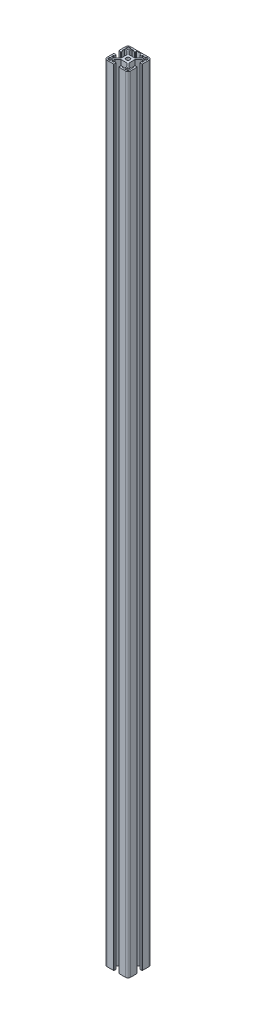
SolidWorks part; units mm, degrees
ref_plane "Front Plane" through (0, 0, 0) normal (0, 0, 1) x (1, 0, 0)
ref_plane "Top Plane" through (0, 0, 0) normal (0, 1, 0) x (1, 0, 0)
ref_plane "Right Plane" through (0, 0, 0) normal (1, 0, 0) x (0, 0, -1)
sketch "Sketch2" plane through (0, 0, 0) normal (0, 1, 0) x (1, 0, 0)
  line L0 (3.6, -15) -> (12, -15)
  line L1 (15, -12) -> (15, -3.6)
  line L2 (14.5, -3.1) -> (12.5, -3.1)
  line L3 (12, -3.6) -> (12, -5.6)
  line L4 (12, -5.6) -> (12.5, -5.6)
  line L5 (13, -6.1) -> (13, -8.25)
  line L6 (13, -8.25) -> (10.4926, -8.25)
  line L7 (9.0784, -7.6642) -> (5.25, -3.8358)
  line L9 (3.8358, -5.25) -> (7.4142, -8.8284)
  line L10 (8, -10.2426) -> (8, -13)
  line L11 (8, -13) -> (6.1, -13)
  line L12 (5.6, -12.5) -> (5.6, -12)
  line L13 (5.6, -12) -> (3.6, -12)
  line L14 (3.1, -12.5) -> (3.1, -14.5)
  line L15 (0, 0) -> (0, 2.5) construction
  line L16 (-3.8358, 5.25) -> (3.8358, 5.25)
  line L17 (-5.25, 3.8358) -> (-5.25, -3.8358)
  line L18 (-3.8358, -5.25) -> (3.8358, -5.25)
  line L19 (5.25, 3.8358) -> (5.25, -3.8358)
  line L20 (-1.7678, 1.7678) -> (8.7215, -8.7215) construction
  line L21 (-1.7678, -1.7678) -> (1.7678, 1.7678) construction
  line L22 (9.5, -9.75) -> (13.25, -9.75)
  line L23 (9.5, -9.75) -> (9.5, -13.5)
  line L24 (9.5, -13.5) -> (11.25, -13.5)
  line L25 (13.25, -9.75) -> (13.25, -11.5)
  line L26 (0, 0) -> (-2.5, 0) construction
  line L27 (-3.1, -12.5) -> (-3.1, -14.5)
  line L28 (-5.6, -12) -> (-3.6, -12)
  line L29 (-5.6, -12.5) -> (-5.6, -12)
  line L30 (-13.25, -9.75) -> (-13.25, -11.5)
  line L31 (-9.5, -13.5) -> (-11.25, -13.5)
  line L32 (-9.5, -9.75) -> (-9.5, -13.5)
  line L33 (-9.5, -9.75) -> (-13.25, -9.75)
  line L34 (-8, -13) -> (-6.1, -13)
  line L35 (-8, -10.2426) -> (-8, -13)
  line L36 (-3.8358, -5.25) -> (-7.4142, -8.8284)
  line L37 (-9.0784, -7.6642) -> (-5.25, -3.8358)
  line L38 (-13, -8.25) -> (-10.4926, -8.25)
  line L39 (-13, -6.1) -> (-13, -8.25)
  line L40 (-12, -5.6) -> (-12.5, -5.6)
  line L41 (-12, -3.6) -> (-12, -5.6)
  line L42 (-14.5, -3.1) -> (-12.5, -3.1)
  line L43 (-15, -12) -> (-15, -3.6)
  line L44 (-3.6, -15) -> (-12, -15)
  line L45 (3.1, 12.5) -> (3.1, 14)
  line L46 (5.6, 12) -> (3.6, 12)
  line L47 (5.6, 12.5) -> (5.6, 12)
  line L48 (-5.6, 12.5) -> (-5.6, 12)
  line L49 (-5.6, 12) -> (-3.6, 12)
  line L50 (-3.1, 12.5) -> (-3.1, 14)
  line L52 (-8, 13) -> (-6.1, 13)
  line L53 (-3.8358, 5.25) -> (-7.4142, 8.8284)
  line L54 (-9.0784, 7.6642) -> (-5.25, 3.8358)
  line L55 (-15, 12) -> (-15, 3.6)
  line L56 (-14.5, 3.1) -> (-12.5, 3.1)
  line L57 (-12, 3.6) -> (-12, 5.6)
  line L58 (-12, 5.6) -> (-12.5, 5.6)
  line L59 (-13, 6.1) -> (-13, 8.25)
  line L60 (-13, 8.25) -> (-10.4926, 8.25)
  line L61 (-8, 10.2426) -> (-8, 13)
  line L62 (-9.5, 9.75) -> (-13.25, 9.75)
  line L63 (-9.5, 9.75) -> (-9.5, 13.5)
  line L64 (-9.5, 13.5) -> (-11.25, 13.5)
  line L65 (-13.25, 9.75) -> (-13.25, 11.5)
  line L66 (13.25, 9.75) -> (13.25, 11.5)
  line L67 (9.5, 13.5) -> (11.25, 13.5)
  line L68 (9.5, 9.75) -> (9.5, 13.5)
  line L69 (9.5, 9.75) -> (13.25, 9.75)
  line L70 (8, 13) -> (6.1, 13)
  line L71 (8, 10.2426) -> (8, 13)
  line L72 (3.8358, 5.25) -> (7.4142, 8.8284)
  line L73 (9.0784, 7.6642) -> (5.25, 3.8358)
  line L74 (13, 8.25) -> (10.4926, 8.25)
  line L75 (13, 6.1) -> (13, 8.25)
  line L76 (12, 5.6) -> (12.5, 5.6)
  line L77 (12, 3.6) -> (12, 5.6)
  line L78 (14.5, 3.1) -> (12.5, 3.1)
  line L79 (15, 12) -> (15, 3.6)
  line L81 (0, 5.25) -> (0, 9.0083) construction
  line L82 (-5.25, 0) -> (-10.2369, 0) construction
  line L83 (12, 15) -> (-12, 15)
  line L86 (-3.1, 14) -> (3.1, 14)
  circle A0 centre (0, 0) radius 2.5
  arc A1 (7.4142, -8.8284) -> (8, -10.2426) centre (6, -10.2426) cw
  arc A2 (10.4926, -8.25) -> (9.0784, -7.6642) centre (10.4926, -6.25) cw
  arc A5 (15, -3.6) -> (14.5, -3.1) centre (14.5, -3.6) ccw
  arc A6 (12.5, -3.1) -> (12, -3.6) centre (12.5, -3.6) ccw
  arc A7 (12.5, -5.6) -> (13, -6.1) centre (12.5, -6.1) cw
  arc A8 (6.1, -13) -> (5.6, -12.5) centre (6.1, -12.5) cw
  arc A9 (3.6, -15) -> (3.1, -14.5) centre (3.6, -14.5) cw
  arc A10 (3.6, -12) -> (3.1, -12.5) centre (3.6, -12.5) ccw
  arc A11 (12, -15) -> (15, -12) centre (12, -12) ccw
  arc A12 (11.25, -13.5) -> (13.25, -11.5) centre (11.25, -11.5) ccw
  arc A13 (-3.6, -15) -> (-3.1, -14.5) centre (-3.6, -14.5) ccw
  arc A14 (-3.6, -12) -> (-3.1, -12.5) centre (-3.6, -12.5) cw
  arc A15 (-6.1, -13) -> (-5.6, -12.5) centre (-6.1, -12.5) ccw
  arc A16 (-11.25, -13.5) -> (-13.25, -11.5) centre (-11.25, -11.5) cw
  arc A17 (-12, -15) -> (-15, -12) centre (-12, -12) cw
  arc A18 (-12.5, -5.6) -> (-13, -6.1) centre (-12.5, -6.1) ccw
  arc A19 (-12.5, -3.1) -> (-12, -3.6) centre (-12.5, -3.6) cw
  arc A20 (-15, -3.6) -> (-14.5, -3.1) centre (-14.5, -3.6) cw
  arc A21 (-10.4926, -8.25) -> (-9.0784, -7.6642) centre (-10.4926, -6.25) ccw
  arc A22 (-7.4142, -8.8284) -> (-8, -10.2426) centre (-6, -10.2426) ccw
  arc A24 (3.6, 12) -> (3.1, 12.5) centre (3.6, 12.5) cw
  arc A25 (6.1, 13) -> (5.6, 12.5) centre (6.1, 12.5) ccw
  arc A26 (-3.6, 12) -> (-3.1, 12.5) centre (-3.6, 12.5) ccw
  arc A28 (-6.1, 13) -> (-5.6, 12.5) centre (-6.1, 12.5) cw
  arc A29 (-7.4142, 8.8284) -> (-8, 10.2426) centre (-6, 10.2426) cw
  arc A30 (-10.4926, 8.25) -> (-9.0784, 7.6642) centre (-10.4926, 6.25) cw
  arc A31 (-15, 3.6) -> (-14.5, 3.1) centre (-14.5, 3.6) ccw
  arc A32 (-12.5, 3.1) -> (-12, 3.6) centre (-12.5, 3.6) ccw
  arc A33 (-12.5, 5.6) -> (-13, 6.1) centre (-12.5, 6.1) cw
  arc A34 (-12, 15) -> (-15, 12) centre (-12, 12) ccw
  arc A35 (-11.25, 13.5) -> (-13.25, 11.5) centre (-11.25, 11.5) ccw
  arc A36 (11.25, 13.5) -> (13.25, 11.5) centre (11.25, 11.5) cw
  arc A37 (12, 15) -> (15, 12) centre (12, 12) cw
  arc A38 (12.5, 5.6) -> (13, 6.1) centre (12.5, 6.1) ccw
  arc A39 (12.5, 3.1) -> (12, 3.6) centre (12.5, 3.6) cw
  arc A40 (15, 3.6) -> (14.5, 3.1) centre (14.5, 3.6) cw
  arc A41 (10.4926, 8.25) -> (9.0784, 7.6642) centre (10.4926, 6.25) ccw
  arc A42 (7.4142, 8.8284) -> (8, 10.2426) centre (6, 10.2426) ccw
  point P34 (13.25, -13.5)
  point P37 (5.6, -12.25)
  point P40 (15, -3.1)
  point P43 (12, -3.1)
  point P50 (3.1, -15)
  point P53 (3.1, -12)
  point P54 (3.1, -13.5)
  point P58 (-3.1, -13.5)
  point P62 (-3.1, -12)
  point P64 (-5.6, -12.25)
  point P97 (-12, -3.1)
  point P98 (-15, -3.1)
  point P99 (-13.25, -13.5)
  point P149 (-13.25, 13.5)
  point P150 (-15, 3.1)
  point P151 (-12, 3.1)
  point P181 (12, 3.1)
  point P182 (15, 3.1)
  point P183 (13.25, 13.5)
  dimension "D1" = 5
  dimension "D22" = 2
  dimension "D23" = 0.5
  dimension "D24" = 3
  dimension "D25" = 2
  dimension "D30" = 7.6716
  dimension "D3" = 30
  dimension "D4" = 30
  dimension "D5" = 1
  dimension "D6" = 3.1
  dimension "D7" = 3
  dimension "D8" = 2
  dimension "D9" = 9.75
  dimension "D10" = 9.75
  dimension "D11" = 3
  dimension "D12" = 2
  dimension "D13" = 6.75
  dimension "D14" = 7
  dimension "D15" = 3.75
  dimension "D16" = 3.75
  dimension "D17" = 1.5
  dimension "D18" = 1.5
  dimension "D19" = 3.1
  dimension "D20" = 2.5
  dimension "D21" = 2.5
  dimension "D26" = 1
  dimension "D27" = 10.5
  dimension "D28" = 10.5
  dimension "D29" = 2
  dimension "D31" = 5.4142
  dimension "D32" = 45
  dimension "D33" = 90
extrude "Boss-Extrude1" add sketch "Sketch2" along normal blind 1000
ref_plane "Ground Level" through (0, -50, 0) normal (0, -1, 0) x (-1, 0, 0)
ref_plane "Profile Locking" through (0, 235, 0) normal (0, -1, 0) x (-1, 0, 0)
ref_plane "Axes platform" through (0, 750, 0) normal (0, -1, 0) x (-1, 0, 0)
ref_plane "Robotino Height" through (0, 250, 0) normal (0, -1, 0) x (-1, 0, 0)
ref_plane "Conveyor Level" through (0, 850, 0) normal (0, -1, 0) x (-1, 0, 0)
ref_plane "TagCamera Height" through (0, 430, 0) normal (0, -1, 0) x (-1, 0, 0)
ref_plane "Drive Assembly height" through (0, 180, 0) normal (0, -1, 0) x (-1, 0, 0)
